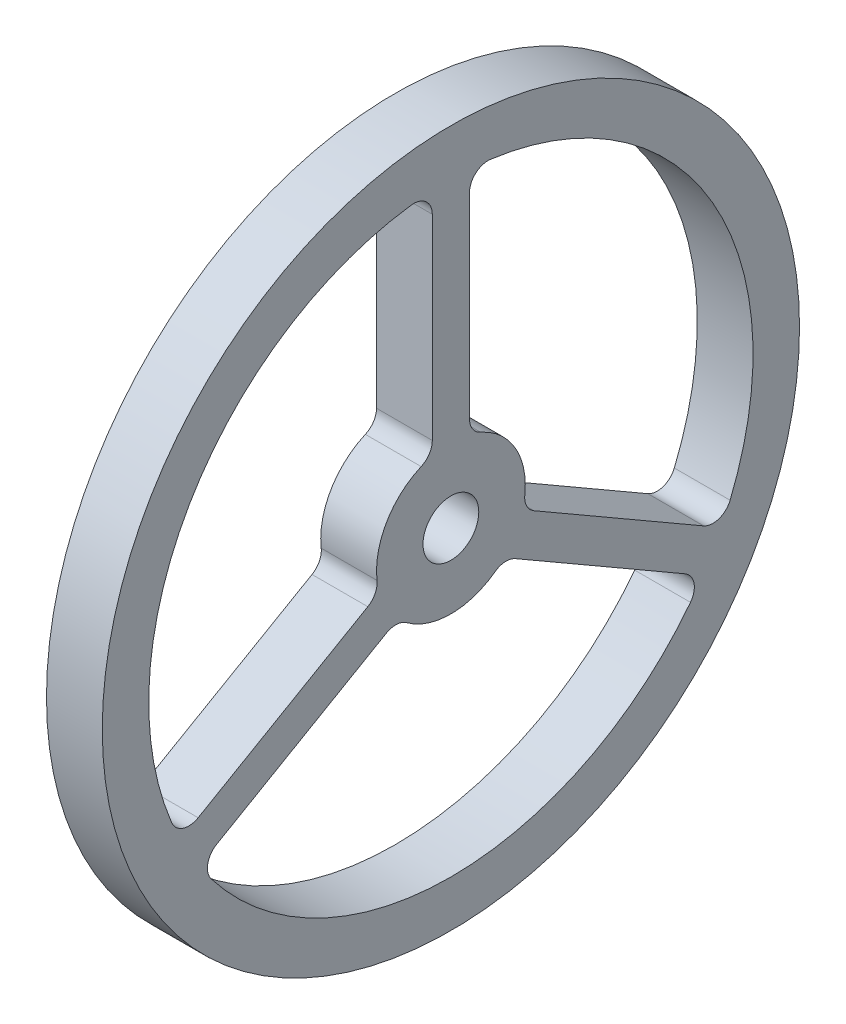
SolidWorks part; units mm, degrees
material "Acrylic (Medium-high impact)"
ref_plane "Front Plane" through (0, 0, 0) normal (0, 0, 1) x (1, 0, 0)
ref_plane "Top Plane" through (0, 0, 0) normal (0, 1, 0) x (1, 0, 0)
ref_plane "Right Plane" through (0, 0, 0) normal (1, 0, 0) x (0, 0, -1)
sketch "Sketch1" plane through (0, 0, 0) normal (1, 0, 0) x (0, 0, -1)
  line L0 (0, 0) -> (0, 37.5) construction
  line L1 (-2, 32.4384) -> (-2, 7.746)
  line L2 (2, 32.4384) -> (2, 7.746)
  line L3 (29.0925, -14.4872) -> (7.7082, -2.1409)
  line L4 (27.0925, -17.9513) -> (5.7082, -5.605)
  line L5 (-27.0925, -17.9513) -> (-5.7082, -5.605)
  line L6 (-29.0925, -14.4872) -> (-7.7082, -2.1409)
  circle A0 centre (0, 0) radius 37.5
  circle A2 centre (0, 0) radius 32.5
  circle A3 centre (0, 0) radius 3
  circle A4 centre (0, 0) radius 8
  point P23 (0, 0)
  dimension "D1" = 75
  dimension "D3" = 6
  dimension "D6" = 4
  dimension "D2" = 5
  dimension "D4" = 5
  dimension "D5" = 3
extrude "Boss-Extrude1" add sketch "Sketch1" along normal blind 6
fillet "Fillet1" radius 2 12 edges at (3, -2.1409, 7.7082) (3, -5.605, 5.7082) (3, -5.605, -5.7082) (3, -2.1409, -7.7082) (3, 7.746, -2) (3, -17.9513, -27.0925) (3, -14.4872, -29.0925) (3, -17.9513, 27.0925) (3, -14.4872, 29.0925) (3, 32.4384, -2) (3, 32.4384, 2) (3, 7.746, 2)
